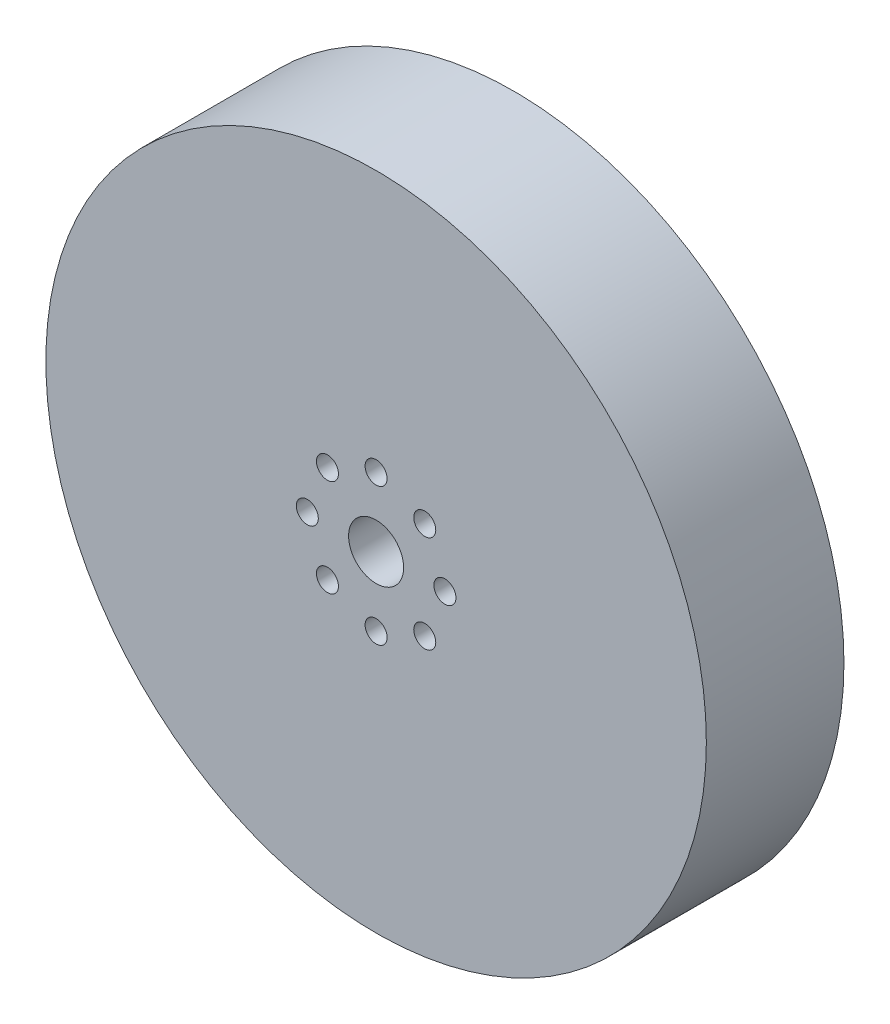
SolidWorks part; units mm, degrees
material "Silicon Rubber"
ref_plane "正面" through (0, 0, 0) normal (0, 0, 1) x (1, 0, 0)
ref_plane "平面" through (0, 0, 0) normal (0, 1, 0) x (1, 0, 0)
ref_plane "右側面" through (0, 0, 0) normal (1, 0, 0) x (0, 0, -1)
sketch "Sketch1" plane through (0, 0, 0) normal (0, 0, 1) x (1, 0, 0)
  circle A0 centre (0, 0) radius 48
  dimension "D1" = 96
extrude "Boss-Extrude1" add sketch "Sketch1" along normal blind 20
sketch "Sketch2" plane through (0, 0, 0) normal (0, 0, -1) x (-1, 0, 0)
  line L0 (0, 0) -> (0, 10) construction
  circle A0 centre (0, 0) radius 4
  circle A1 centre (0, 10) radius 1.6
  circle A2 centre (7.0711, 7.0711) radius 1.6
  circle A3 centre (10, 0) radius 1.6
  circle A4 centre (7.0711, -7.0711) radius 1.6
  circle A5 centre (0, -10) radius 1.6
  circle A6 centre (-7.0711, -7.0711) radius 1.6
  circle A7 centre (-10, 0) radius 1.6
  circle A8 centre (-7.0711, 7.0711) radius 1.6
  point P21 (0, 0)
  dimension "D1" = 8
  dimension "D2" = 3.2
  dimension "D4" = 10
  dimension "D3" = 8
extrude "Cut-Extrude1" cut sketch "Sketch2" against normal up to next
